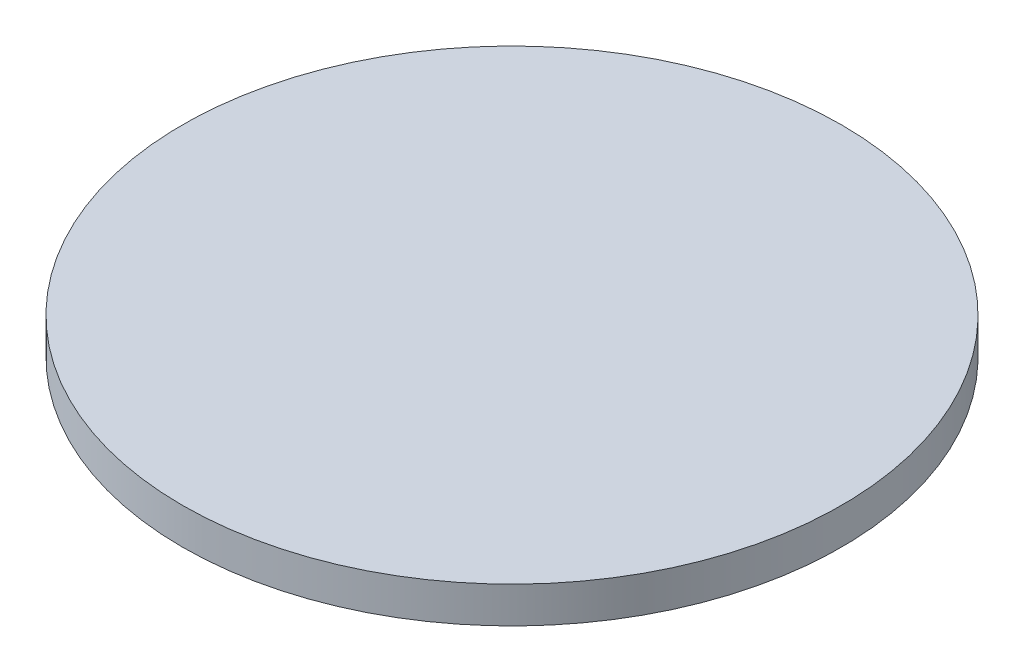
SolidWorks part; units mm, degrees
ref_plane "Front Plane" through (0, 0, 0) normal (0, 0, 1) x (1, 0, 0)
ref_plane "Top Plane" through (0, 0, 0) normal (0, 1, 0) x (1, 0, 0)
ref_plane "Right Plane" through (0, 0, 0) normal (1, 0, 0) x (0, 0, -1)
sketch "Sketch1" plane through (0, 0, 0) normal (0, 1, 0) x (1, 0, 0)
  circle A0 centre (0, 0) radius 27.3
  dimension "D1" = 54.6
extrude "Boss-Extrude1" add sketch "Sketch1" along normal blind 3
